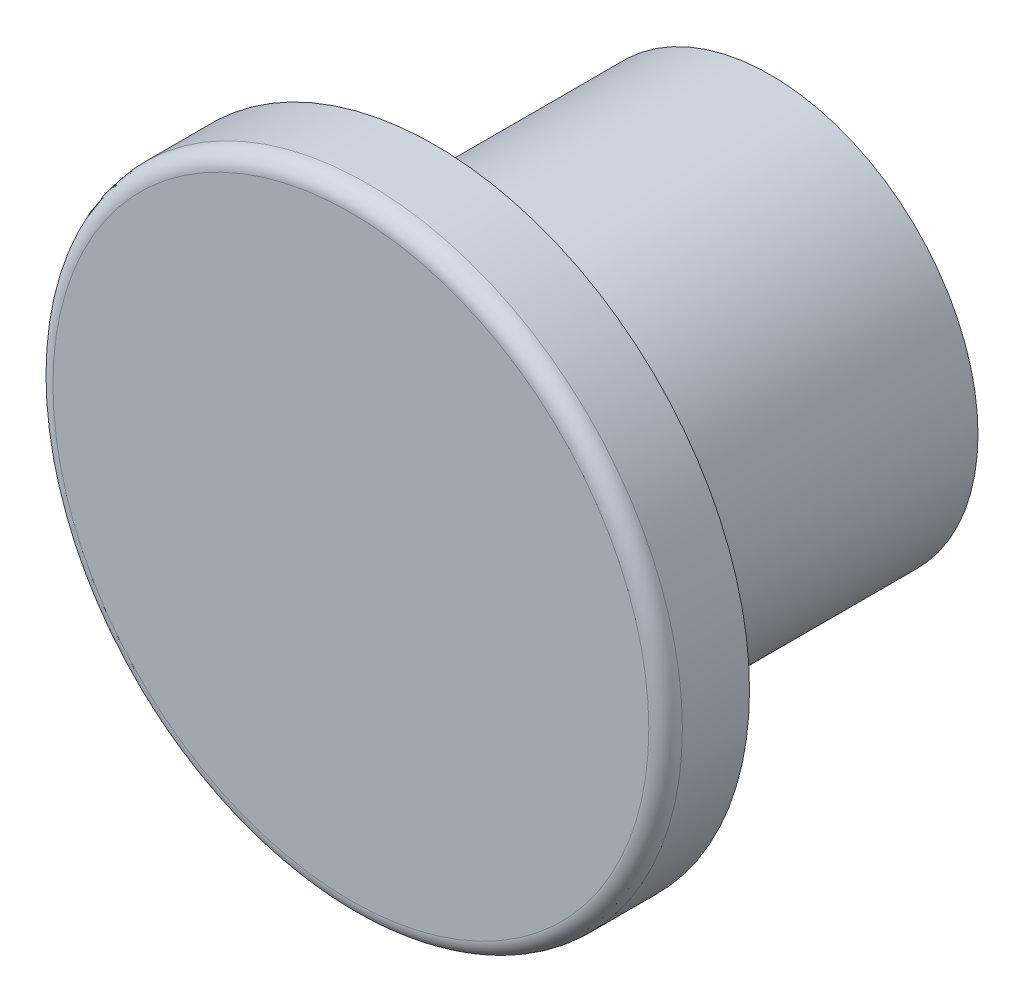
SolidWorks part; units mm, degrees
material "AISI Type A2 Tool Steel"
ref_plane "Front Plane" through (0, 0, 0) normal (0, 0, 1) x (1, 0, 0)
ref_plane "Top Plane" through (0, 0, 0) normal (0, 1, 0) x (1, 0, 0)
ref_plane "Right Plane" through (0, 0, 0) normal (1, 0, 0) x (0, 0, -1)
sketch "Sketch1" plane through (0, 0, 0) normal (0, 0, 1) x (1, 0, 0)
  circle A0 centre (0, 0) radius 7.5
  dimension "D1" = 15
extrude "Boss-Extrude1" add sketch "Sketch1" against normal blind 2
sketch "Sketch2" plane through (0, 0, 0) normal (0, 0, 1) x (1, 0, 0)
  circle A0 centre (0, 0) radius 4.945
  dimension "D1" = 9.89
extrude "Boss-Extrude2" add sketch "Sketch2" against normal blind 10
fillet "Fillet2" radius 0.4 1 edges at (7.5, 0, 0)
